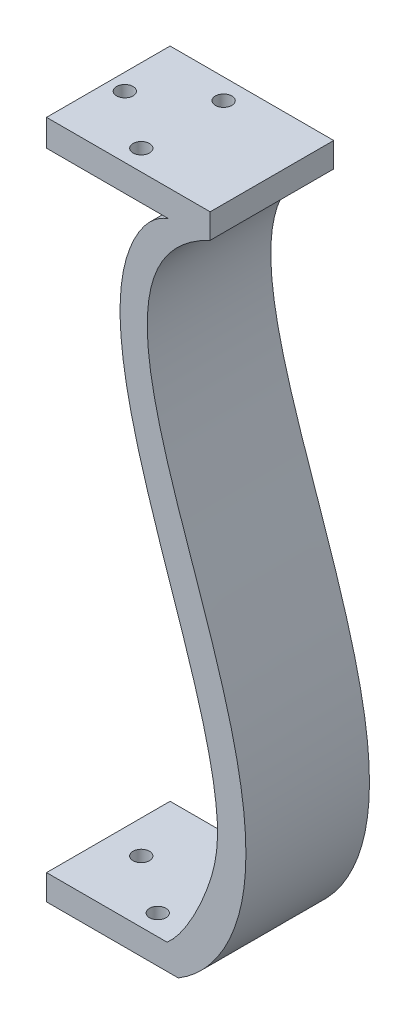
SolidWorks part; units mm, degrees
ref_plane "Front" through (0, 0, 0) normal (0, 0, 1) x (1, 0, 0)
ref_plane "Top" through (0, 0, 0) normal (0, 1, 0) x (1, 0, 0)
ref_plane "Right" through (0, 0, 0) normal (1, 0, 0) x (0, 0, -1)
sketch "Sketch1" plane through (0, 0, 0) normal (0, 1, 0) x (1, 0, 0)
  line L1 (0, 0) -> (-50, 0)
  line L2 (0, 0) -> (0, 30)
  line L3 (0, 30) -> (-50, 30)
  line L4 (-50, 0) -> (-50, 30)
  dimension "D1" = 50
  dimension "D2" = 30
extrude "block" add sketch "Sketch1" along normal blind 165
sketch "Sketch2" plane through (0, 0, 0) normal (0, 0, 1) x (1, 0, 0)
  line L1 (-50, 0) -> (0, 0) construction
  line L2 (-10.2669, 159) -> (-10.2669, 165)
  line L3 (-50, 165) -> (0, 165) construction
  line L4 (-18, 0) -> (0, 0)
  line L5 (0, 0) -> (0, 165)
  line L6 (0, 165) -> (-10.2669, 165)
  spline S0 degree 3 poles (-18, 0) (-10.6551, 4.4325) (21.0969, 53.2889) (-53.3339, 138.2792) (-10.2669, 159) knots 0 0 0 0 0.153176 1 1 1 1
  point P2 (0, 0)
  dimension "D1" = 6
  dimension "D2" = 18
extrude "Cut-Extrude1" cut sketch "Sketch2" against normal through all
sketch "Sketch3" plane through (0, 0, 0) normal (0, 0, 1) x (1, 0, 0)
  line L1 (-20.7199, 6.1656) -> (-50, 6.1656)
  line L2 (-50, 165) -> (-50, 0) construction
  line L3 (-20.3559, 158.5) -> (-50, 158.5)
  line L5 (-50, 165) -> (-10.2669, 165) construction
  spline S0 degree 3 poles (-20.7199, 6.1656) (-16.4171, 9.8799) (-8.5946, 25.2925) (-7.1245, 64.8232) (-46.2844, 128.9244) (-24.282, 157.1562) (-20.3559, 158.5) knots 0.052573 0.052573 0.052573 0.052573 0.159087 0.252212 0.902535 1 1 1 1
  dimension "D1" = 6.5
extrude "Cut-Extrude2" cut sketch "Sketch3" against normal through all and the other way through all
sketch "Sketch4" plane through (0, 0, 0) normal (0, -1, 0) x (1, 0, 0)
  line L0 (-50, -15) -> (-23.0693, -15) construction
  line L1 (-50, -30) -> (-50, 0) construction
  line L3 (-28, -3.0213) -> (-18, -3.0213) construction
  line L5 (-18, -30) -> (-18, 0) construction
  circle A0 centre (-42, -15) radius 2
  circle A1 centre (-28, -25) radius 2
  circle A2 centre (-28, -5) radius 2
  dimension "D1" = 4
  dimension "D3" = 10
  dimension "D2" = 10
  dimension "D4" = 14
extrude "Cut-Extrude3" cut sketch "Sketch4" against normal up to next
sketch "Sketch6" plane through (0, 165, 0) normal (0, 1, 0) x (1, 0, 0)
  line L0 (-50, 15) -> (-15.2551, 15) construction
  line L1 (-50, 30) -> (-50, 0) construction
  circle A0 centre (-46, 15) radius 2
  circle A1 centre (-32, 25) radius 2
  circle A2 centre (-32, 5) radius 2
  dimension "D1" = 4
  dimension "D2" = 4
  dimension "D3" = 4
  dimension "D5" = 20
  dimension "D4" = 14
  dimension "D6" = 4
extrude "Cut-Extrude10" cut sketch "Sketch6" against normal up to next
